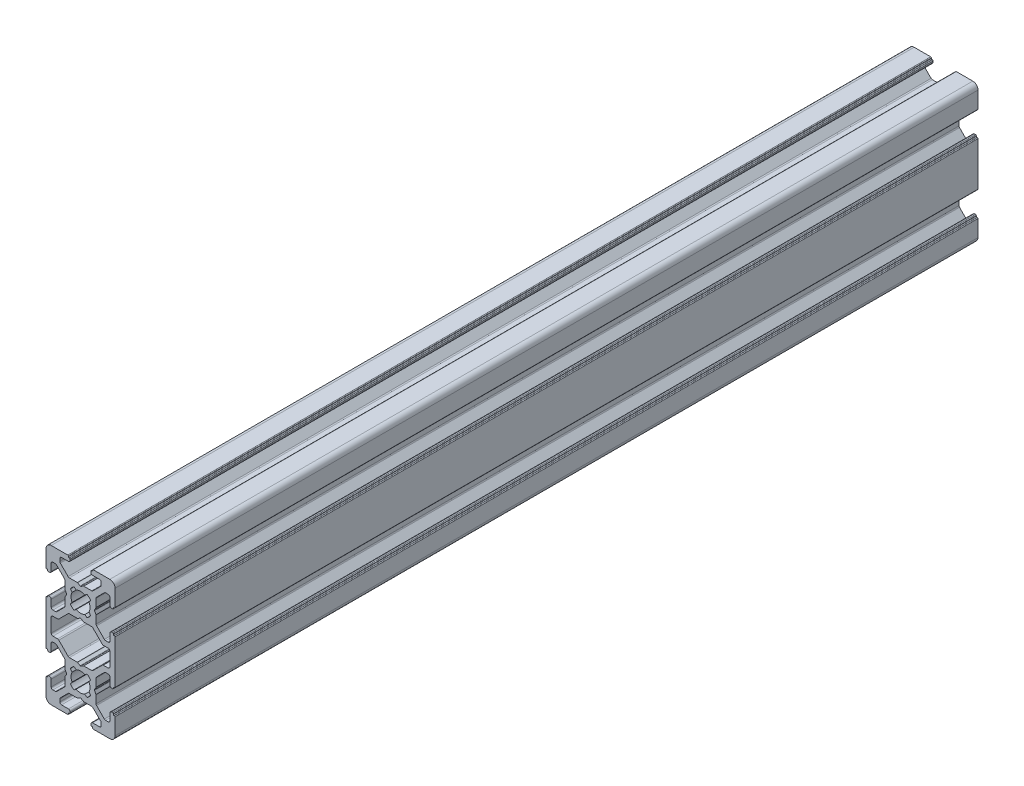
SolidWorks part; units mm, degrees
ref_plane "Front Plane" through (0, 0, 0) normal (0, 0, 1) x (1, 0, 0)
ref_plane "Top Plane" through (0, 0, 0) normal (0, 1, 0) x (1, 0, 0)
ref_plane "Right Plane" through (0, 0, 0) normal (1, 0, 0) x (0, 0, -1)
sketch "Sketch1" plane through (0, 0, 0) normal (0, 0, 1) x (1, 0, 0)
  line L0 (10, -3.75) -> (10, -8.5)
  line L1 (8.5, -3.55) -> (8.5, -5.5)
  line L2 (9.5, -3.25) -> (9.5, -3.35)
  line L3 (9.7, -3.55) -> (9.8, -3.55)
  line L4 (9, -3.05) -> (9.3, -3.05)
  line L5 (9.7, 3.45) -> (9.8, 3.45)
  line L6 (9.5, 3.15) -> (9.5, 3.25)
  line L7 (9, 2.95) -> (9.3, 2.95)
  line L8 (8.5, 3.45) -> (8.5, 5.5)
  line L9 (10, 3.65) -> (10, 10)
  line L10 (-9.7, 3.45) -> (-9.8, 3.45)
  line L11 (-9.5, 3.15) -> (-9.5, 3.25)
  line L12 (-9, 2.95) -> (-9.3, 2.95)
  line L13 (-8.5, 3.45) -> (-8.5, 5.5)
  line L14 (-10, 3.65) -> (-10, 10)
  line L15 (-9.7, -3.55) -> (-9.8, -3.55)
  line L16 (-9.5, -3.25) -> (-9.5, -3.35)
  line L17 (-9, -3.05) -> (-9.3, -3.05)
  line L18 (-8.5, -3.55) -> (-8.5, -5.5)
  line L19 (-10, -3.75) -> (-10, -8.5)
  line L20 (-3.7, -10) -> (-8.5, -10)
  line L21 (-3.5, -8.5) -> (-5.5, -8.5)
  line L22 (-3.2, -9.5) -> (-3.3, -9.5)
  line L23 (-3.5, -9.7) -> (-3.5, -9.8)
  line L24 (-3, -9) -> (-3, -9.3)
  line L25 (3.7, -10) -> (8.5, -10)
  line L26 (3.5, -9.7) -> (3.5, -9.8)
  line L27 (3.2, -9.5) -> (3.3, -9.5)
  line L28 (3, -9) -> (3, -9.3)
  line L29 (3.5, -8.5) -> (5.5, -8.5)
  line L30 (-9.7, 23.5) -> (-9.8, 23.5)
  line L31 (-9.5, 23.2) -> (-9.5, 23.3)
  line L32 (-9, 23) -> (-9.3, 23)
  line L33 (-8.5, 23.5) -> (-8.5, 25.55)
  line L34 (-10, 23.7) -> (-10, 28.5)
  line L35 (-9.7, 16.5) -> (-9.8, 16.5)
  line L36 (-9.5, 16.8) -> (-9.5, 16.7)
  line L37 (-9, 17) -> (-9.3, 17)
  line L38 (-8.5, 16.5) -> (-8.5, 14.55)
  line L39 (-10, 16.3) -> (-10, 10)
  line L40 (10, 16.3) -> (10, 10)
  line L41 (8.5, 16.5) -> (8.5, 14.5)
  line L42 (9.5, 16.8) -> (9.5, 16.7)
  line L43 (9.7, 16.5) -> (9.8, 16.5)
  line L44 (9, 17) -> (9.3, 17)
  line L45 (9.7, 23.5) -> (9.8, 23.5)
  line L46 (9.5, 23.2) -> (9.5, 23.3)
  line L47 (9, 23) -> (9.3, 23)
  line L48 (8.5, 23.5) -> (8.5, 25.5)
  line L49 (10, 23.7) -> (10, 28.5)
  line L50 (-3.7, 30) -> (-8.5, 30)
  line L51 (-3.5, 28.5) -> (-5.5, 28.5)
  line L52 (-3, 29) -> (-3, 29.3)
  line L53 (-3.2, 29.5) -> (-3.3, 29.5)
  line L54 (-3.5, 29.7) -> (-3.5, 29.8)
  line L55 (3.7, 30) -> (8.5, 30)
  line L56 (3.5, 28.5) -> (5.5, 28.5)
  line L57 (3.2, 29.5) -> (3.3, 29.5)
  line L58 (3.5, 29.7) -> (3.5, 29.8)
  line L59 (3, 29) -> (3, 29.3)
  line L60 (2.4453, 18.7418) -> (2.9477, 18.1129)
  line L61 (1.2582, 17.5547) -> (1.8871, 17.0523)
  line L62 (-1.2582, 17.5547) -> (-1.8871, 17.0523)
  line L63 (-2.4453, 18.7418) -> (-2.9477, 18.1129)
  line L64 (-2.4453, 21.2582) -> (-2.9477, 21.8871)
  line L65 (-1.2582, 22.4453) -> (-1.8871, 22.9477)
  line L66 (3.5859, 24.6465) -> (5.8536, 26.9142)
  line L67 (4.6464, 23.5858) -> (6.9142, 25.8536)
  line L68 (4.5, 23.2322) -> (4.5, 20.9536)
  line L69 (4.4732, 20.8536) -> (4.0381, 20.1)
  line L70 (4.4732, 19.1464) -> (4.0381, 19.9)
  line L71 (4.5, 16.7678) -> (4.5, 19.0464)
  line L72 (7.2678, 26) -> (8, 26)
  line L73 (7.2678, 14) -> (8, 14)
  line L74 (2.4453, 21.2582) -> (2.9477, 21.8871)
  line L75 (4.6464, 16.4142) -> (6.9142, 14.1464)
  line L76 (3.2322, 15.5) -> (0.9536, 15.5)
  line L77 (0.8536, 15.5268) -> (0.1, 15.9619)
  line L78 (-0.8536, 15.5268) -> (-0.1, 15.9619)
  line L79 (-3.2322, 15.5) -> (-0.9536, 15.5)
  line L80 (3.5858, 15.3535) -> (6.2929, 12.6464)
  line L81 (-3.5858, 15.3535) -> (-6.2929, 12.6464)
  line L82 (-4.5, 16.7678) -> (-4.5, 19.0464)
  line L83 (-4.4732, 19.1464) -> (-4.0381, 19.9)
  line L84 (-4.4732, 20.8536) -> (-4.0381, 20.1)
  line L85 (-4.5, 23.2322) -> (-4.5, 20.9536)
  line L86 (-7.2178, 14.05) -> (-8, 14.05)
  line L87 (-7.3178, 26.05) -> (-8, 26.05)
  line L88 (-4.6464, 16.4142) -> (-6.8642, 14.1964)
  line L89 (-4.6464, 23.5858) -> (-6.9642, 25.9036)
  line L90 (1.2582, 22.4453) -> (1.8871, 22.9477)
  line L91 (-3.5859, 24.6465) -> (-5.8536, 26.9142)
  line L92 (6, 27.2678) -> (6, 28)
  line L93 (-6, 27.2678) -> (-6, 28)
  line L94 (3.2323, 24.5) -> (0.9537, 24.5)
  line L95 (0.8537, 24.4733) -> (0.1, 24.0381)
  line L96 (-0.8537, 24.4733) -> (-0.1, 24.0381)
  line L97 (-3.2323, 24.5) -> (-0.9537, 24.5)
  line L98 (-3.2322, -4.5) -> (-0.9536, -4.5)
  line L99 (-0.8536, -4.4732) -> (-0.1, -4.0381)
  line L100 (0.8536, -4.4732) -> (0.1, -4.0381)
  line L101 (3.2322, -4.5) -> (0.9536, -4.5)
  line L102 (-6, -7.2678) -> (-6, -8)
  line L103 (6, -7.2678) -> (6, -8)
  line L104 (-3.5858, -4.6464) -> (-5.8536, -6.9142)
  line L105 (1.2582, -2.4453) -> (1.8871, -2.9477)
  line L106 (-4.6464, -3.5858) -> (-6.9142, -5.8536)
  line L107 (-4.6464, 3.5858) -> (-6.9142, 5.8536)
  line L108 (-7.2678, -6) -> (-8, -6)
  line L109 (-7.2678, 6) -> (-8, 6)
  line L110 (-4.5, -3.2322) -> (-4.5, -0.9536)
  line L111 (-4.4732, -0.8536) -> (-4.0381, -0.1)
  line L112 (-4.4732, 0.8536) -> (-4.0381, 0.1)
  line L113 (-4.5, 3.2322) -> (-4.5, 0.9536)
  line L114 (-3.586, 4.6466) -> (-6.2929, 7.3535)
  line L115 (3.586, 4.6466) -> (6.2929, 7.3535)
  line L116 (-3.2324, 4.5001) -> (-0.9538, 4.5001)
  line L117 (-0.8538, 4.4733) -> (-0.1, 4.0381)
  line L118 (0.8538, 4.4733) -> (0.1, 4.0381)
  line L119 (3.2324, 4.5001) -> (0.9538, 4.5001)
  line L120 (4.6464, 3.5858) -> (6.9142, 5.8536)
  line L121 (2.4453, -1.2582) -> (2.9477, -1.8871)
  line L122 (7.2678, 6) -> (8, 6)
  line L123 (7.2678, -6) -> (8, -6)
  line L124 (4.5, 3.2322) -> (4.5, 0.9536)
  line L125 (4.4732, 0.8536) -> (4.0381, 0.1)
  line L126 (4.4732, -0.8536) -> (4.0381, -0.1)
  line L127 (4.5, -3.2322) -> (4.5, -0.9536)
  line L128 (4.6464, -3.5858) -> (6.9142, -5.8536)
  line L129 (3.5858, -4.6464) -> (5.8536, -6.9142)
  line L130 (-1.2582, -2.4453) -> (-1.8871, -2.9477)
  line L131 (-2.4453, -1.2582) -> (-2.9477, -1.8871)
  line L132 (-2.4453, 1.2582) -> (-2.9477, 1.8871)
  line L133 (-1.2582, 2.4453) -> (-1.8871, 2.9477)
  line L134 (1.2582, 2.4453) -> (1.8871, 2.9477)
  line L135 (2.4453, 1.2582) -> (2.9477, 1.8871)
  line L136 (6.6464, 12.5) -> (8, 12.5)
  line L137 (8.5, 8) -> (8.5, 12)
  line L138 (6.6464, 7.5) -> (8, 7.5)
  line L139 (-6.6464, 7.5) -> (-8, 7.5)
  line L140 (-8.5, 8) -> (-8.5, 12)
  line L141 (-6.6464, 12.5) -> (-8, 12.5)
  line L142 (0, 33.3296) -> (0, -13.4112) construction
  line L143 (-17.1897, 10) -> (16.9575, 10) construction
  line L144 (-17.1897, 0) -> (16.9575, 0) construction
  line L145 (-17.1897, 20) -> (16.9575, 20) construction
  arc A0 (9.5, -3.25) -> (9.3, -3.05) centre (9.3, -3.25) ccw
  arc A1 (10, -3.75) -> (9.8, -3.55) centre (9.8, -3.75) ccw
  arc A2 (9.5, -3.35) -> (9.7, -3.55) centre (9.7, -3.35) ccw
  arc A3 (9, -3.05) -> (8.5, -3.55) centre (9, -3.55) ccw
  arc A4 (9.7, 3.45) -> (9.5, 3.25) centre (9.7, 3.25) ccw
  arc A5 (9.8, 3.45) -> (10, 3.65) centre (9.8, 3.65) ccw
  arc A6 (9.3, 2.95) -> (9.5, 3.15) centre (9.3, 3.15) ccw
  arc A7 (8.5, 3.45) -> (9, 2.95) centre (9, 3.45) ccw
  arc A8 (-9.5, 3.25) -> (-9.7, 3.45) centre (-9.7, 3.25) ccw
  arc A9 (-10, 3.65) -> (-9.8, 3.45) centre (-9.8, 3.65) ccw
  arc A10 (-9.5, 3.15) -> (-9.3, 2.95) centre (-9.3, 3.15) ccw
  arc A11 (-9, 2.95) -> (-8.5, 3.45) centre (-9, 3.45) ccw
  arc A12 (-9.7, -3.55) -> (-9.5, -3.35) centre (-9.7, -3.35) ccw
  arc A13 (-9.8, -3.55) -> (-10, -3.75) centre (-9.8, -3.75) ccw
  arc A14 (-9.3, -3.05) -> (-9.5, -3.25) centre (-9.3, -3.25) ccw
  arc A15 (-8.5, -3.55) -> (-9, -3.05) centre (-9, -3.55) ccw
  arc A16 (-3.2, -9.5) -> (-3, -9.3) centre (-3.2, -9.3) ccw
  arc A17 (-3.7, -10) -> (-3.5, -9.8) centre (-3.7, -9.8) ccw
  arc A18 (-3.3, -9.5) -> (-3.5, -9.7) centre (-3.3, -9.7) ccw
  arc A19 (-3, -9) -> (-3.5, -8.5) centre (-3.5, -9) ccw
  arc A20 (3.5, -9.7) -> (3.3, -9.5) centre (3.3, -9.7) ccw
  arc A21 (3.5, -9.8) -> (3.7, -10) centre (3.7, -9.8) ccw
  arc A22 (3, -9.3) -> (3.2, -9.5) centre (3.2, -9.3) ccw
  arc A23 (3.5, -8.5) -> (3, -9) centre (3.5, -9) ccw
  arc A24 (-9.5, 23.3) -> (-9.7, 23.5) centre (-9.7, 23.3) ccw
  arc A25 (-10, 23.7) -> (-9.8, 23.5) centre (-9.8, 23.7) ccw
  arc A26 (-9.5, 23.2) -> (-9.3, 23) centre (-9.3, 23.2) ccw
  arc A27 (-9, 23) -> (-8.5, 23.5) centre (-9, 23.5) ccw
  arc A28 (-9.7, 16.5) -> (-9.5, 16.7) centre (-9.7, 16.7) ccw
  arc A29 (-9.8, 16.5) -> (-10, 16.3) centre (-9.8, 16.3) ccw
  arc A30 (-9.3, 17) -> (-9.5, 16.8) centre (-9.3, 16.8) ccw
  arc A31 (-8.5, 16.5) -> (-9, 17) centre (-9, 16.5) ccw
  arc A32 (9.5, 16.8) -> (9.3, 17) centre (9.3, 16.8) ccw
  arc A33 (10, 16.3) -> (9.8, 16.5) centre (9.8, 16.3) ccw
  arc A34 (9.5, 16.7) -> (9.7, 16.5) centre (9.7, 16.7) ccw
  arc A35 (9, 17) -> (8.5, 16.5) centre (9, 16.5) ccw
  arc A36 (9.7, 23.5) -> (9.5, 23.3) centre (9.7, 23.3) ccw
  arc A37 (9.8, 23.5) -> (10, 23.7) centre (9.8, 23.7) ccw
  arc A38 (9.3, 23) -> (9.5, 23.2) centre (9.3, 23.2) ccw
  arc A39 (8.5, 23.5) -> (9, 23) centre (9, 23.5) ccw
  arc A40 (-3, 29.3) -> (-3.2, 29.5) centre (-3.2, 29.3) ccw
  arc A41 (-3.5, 29.8) -> (-3.7, 30) centre (-3.7, 29.8) ccw
  arc A42 (-3.5, 29.7) -> (-3.3, 29.5) centre (-3.3, 29.7) ccw
  arc A43 (-3.5, 28.5) -> (-3, 29) centre (-3.5, 29) ccw
  arc A44 (3.2, 29.5) -> (3, 29.3) centre (3.2, 29.3) ccw
  arc A45 (3.7, 30) -> (3.5, 29.8) centre (3.7, 29.8) ccw
  arc A46 (3.3, 29.5) -> (3.5, 29.7) centre (3.3, 29.7) ccw
  arc A47 (3, 29) -> (3.5, 28.5) centre (3.5, 29) ccw
  arc A48 (2.4453, 18.7418) -> (2.4453, 21.2582) centre (0, 20) ccw
  arc A49 (-1.2582, 17.5547) -> (1.2582, 17.5547) centre (0, 20) ccw
  arc A50 (-2.4453, 21.2582) -> (-2.4453, 18.7418) centre (0, 20) ccw
  arc A51 (1.8871, 17.0523) -> (2.9477, 18.1129) centre (0, 20) ccw
  arc A52 (-2.9477, 18.1129) -> (-1.8871, 17.0523) centre (0, 20) ccw
  arc A53 (-1.8871, 22.9477) -> (-2.9477, 21.8871) centre (0, 20) ccw
  arc A54 (2.9477, 21.8871) -> (1.8871, 22.9477) centre (0, 20) ccw
  arc A55 (4.0381, 20.1) -> (4.0381, 19.9) centre (4.2113, 20) ccw
  arc A56 (4.5, 19.0464) -> (4.4732, 19.1464) centre (4.3, 19.0464) ccw
  arc A57 (4.4732, 20.8536) -> (4.5, 20.9536) centre (4.3, 20.9536) ccw
  arc A58 (6.9142, 14.1464) -> (7.2678, 14) centre (7.2678, 14.5) ccw
  arc A59 (4.5, 16.7678) -> (4.6464, 16.4142) centre (5, 16.7678) ccw
  arc A60 (4.6464, 23.5858) -> (4.5, 23.2322) centre (5, 23.2322) ccw
  arc A61 (7.2678, 26) -> (6.9142, 25.8536) centre (7.2678, 25.5) ccw
  arc A62 (0.1, 15.9619) -> (-0.1, 15.9619) centre (0, 15.7887) ccw
  arc A63 (-0.9536, 15.5) -> (-0.8536, 15.5268) centre (-0.9536, 15.7) ccw
  arc A64 (0.8536, 15.5268) -> (0.9536, 15.5) centre (0.9536, 15.7) ccw
  arc A65 (-3.2322, 15.5) -> (-3.5858, 15.3535) centre (-3.2322, 15) ccw
  arc A66 (3.5858, 15.3535) -> (3.2322, 15.5) centre (3.2322, 15) ccw
  arc A67 (-4.0381, 19.9) -> (-4.0381, 20.1) centre (-4.2113, 20) ccw
  arc A68 (-4.5, 20.9536) -> (-4.4732, 20.8536) centre (-4.3, 20.9536) ccw
  arc A69 (-4.4732, 19.1464) -> (-4.5, 19.0464) centre (-4.3, 19.0464) ccw
  arc A70 (-6.9642, 25.9036) -> (-7.3178, 26.05) centre (-7.3178, 25.55) ccw
  arc A71 (-4.5, 23.2322) -> (-4.6464, 23.5858) centre (-5, 23.2322) ccw
  arc A72 (-4.6464, 16.4142) -> (-4.5, 16.7678) centre (-5, 16.7678) ccw
  arc A73 (-7.2178, 14.05) -> (-6.8642, 14.1964) centre (-7.2178, 14.55) ccw
  arc A74 (-6, 27.2678) -> (-5.8536, 26.9142) centre (-5.5, 27.2678) ccw
  arc A75 (-3.5859, 24.6465) -> (-3.2323, 24.5) centre (-3.2323, 25) ccw
  arc A76 (3.2323, 24.5) -> (3.5859, 24.6465) centre (3.2323, 25) ccw
  arc A77 (5.8536, 26.9142) -> (6, 27.2678) centre (5.5, 27.2678) ccw
  arc A78 (8.5, 25.5) -> (8, 26) centre (8, 25.5) ccw
  arc A79 (10, 28.5) -> (8.5, 30) centre (8.5, 28.5) ccw
  arc A80 (8, 14) -> (8.5, 14.5) centre (8, 14.5) ccw
  arc A81 (-8.5, 14.55) -> (-8, 14.05) centre (-8, 14.55) ccw
  arc A82 (-8, 26.05) -> (-8.5, 25.55) centre (-8, 25.55) ccw
  arc A83 (6, 28) -> (5.5, 28.5) centre (5.5, 28) ccw
  arc A84 (-8.5, 30) -> (-10, 28.5) centre (-8.5, 28.5) ccw
  arc A85 (-5.5, 28.5) -> (-6, 28) centre (-5.5, 28) ccw
  arc A86 (-0.8537, 24.4733) -> (-0.9537, 24.5) centre (-0.9537, 24.3) ccw
  arc A87 (0.9537, 24.5) -> (0.8537, 24.4733) centre (0.9537, 24.3) ccw
  arc A88 (-0.1, 24.0381) -> (0.1, 24.0381) centre (0, 24.2113) ccw
  arc A89 (1.2582, 22.4453) -> (-1.2582, 22.4453) centre (0, 20) ccw
  arc A90 (-1.2582, -2.4453) -> (1.2582, -2.4453) centre (0, 0) ccw
  arc A91 (0.1, -4.0381) -> (-0.1, -4.0381) centre (0, -4.2113) ccw
  arc A92 (0.8536, -4.4732) -> (0.9536, -4.5) centre (0.9536, -4.3) ccw
  arc A93 (-0.9536, -4.5) -> (-0.8536, -4.4732) centre (-0.9536, -4.3) ccw
  arc A94 (-6, -8) -> (-5.5, -8.5) centre (-5.5, -8) ccw
  arc A95 (-10, -8.5) -> (-8.5, -10) centre (-8.5, -8.5) ccw
  arc A96 (5.5, -8.5) -> (6, -8) centre (5.5, -8) ccw
  arc A97 (-8.5, -5.5) -> (-8, -6) centre (-8, -5.5) ccw
  arc A98 (-8, 6) -> (-8.5, 5.5) centre (-8, 5.5) ccw
  arc A99 (8.5, 5.5) -> (8, 6) centre (8, 5.5) ccw
  arc A100 (8.5, -10) -> (10, -8.5) centre (8.5, -8.5) ccw
  arc A101 (8, -6) -> (8.5, -5.5) centre (8, -5.5) ccw
  arc A102 (6, -7.2678) -> (5.8536, -6.9142) centre (5.5, -7.2678) ccw
  arc A103 (3.5858, -4.6464) -> (3.2322, -4.5) centre (3.2322, -5) ccw
  arc A104 (-3.2322, -4.5) -> (-3.5858, -4.6464) centre (-3.2322, -5) ccw
  arc A105 (-5.8536, -6.9142) -> (-6, -7.2678) centre (-5.5, -7.2678) ccw
  arc A106 (-6.9142, 5.8536) -> (-7.2678, 6) centre (-7.2678, 5.5) ccw
  arc A107 (-4.5, 3.2322) -> (-4.6464, 3.5858) centre (-5, 3.2322) ccw
  arc A108 (-4.6464, -3.5858) -> (-4.5, -3.2322) centre (-5, -3.2322) ccw
  arc A109 (-7.2678, -6) -> (-6.9142, -5.8536) centre (-7.2678, -5.5) ccw
  arc A110 (-4.5, 0.9536) -> (-4.4732, 0.8536) centre (-4.3, 0.9536) ccw
  arc A111 (-4.4732, -0.8536) -> (-4.5, -0.9536) centre (-4.3, -0.9536) ccw
  arc A112 (-4.0381, -0.1) -> (-4.0381, 0.1) centre (-4.2113, 0) ccw
  arc A113 (3.2324, 4.5001) -> (3.586, 4.6466) centre (3.2324, 5.0001) ccw
  arc A114 (-3.586, 4.6466) -> (-3.2324, 4.5001) centre (-3.2324, 5.0001) ccw
  arc A115 (0.9538, 4.5001) -> (0.8538, 4.4733) centre (0.9538, 4.3001) ccw
  arc A116 (-0.8538, 4.4733) -> (-0.9538, 4.5001) centre (-0.9538, 4.3001) ccw
  arc A117 (-0.1, 4.0381) -> (0.1, 4.0381) centre (0, 4.2113) ccw
  arc A118 (6.9142, -5.8536) -> (7.2678, -6) centre (7.2678, -5.5) ccw
  arc A119 (4.5, -3.2322) -> (4.6464, -3.5858) centre (5, -3.2322) ccw
  arc A120 (4.6464, 3.5858) -> (4.5, 3.2322) centre (5, 3.2322) ccw
  arc A121 (7.2678, 6) -> (6.9142, 5.8536) centre (7.2678, 5.5) ccw
  arc A122 (4.5, -0.9536) -> (4.4732, -0.8536) centre (4.3, -0.9536) ccw
  arc A123 (4.4732, 0.8536) -> (4.5, 0.9536) centre (4.3, 0.9536) ccw
  arc A124 (4.0381, 0.1) -> (4.0381, -0.1) centre (4.2113, 0) ccw
  arc A125 (1.8871, -2.9477) -> (2.9477, -1.8871) centre (0, 0) ccw
  arc A126 (-2.9477, -1.8871) -> (-1.8871, -2.9477) centre (0, 0) ccw
  arc A127 (-1.8871, 2.9477) -> (-2.9477, 1.8871) centre (0, 0) ccw
  arc A128 (2.9477, 1.8871) -> (1.8871, 2.9477) centre (0, 0) ccw
  arc A129 (-2.4453, 1.2582) -> (-2.4453, -1.2582) centre (0, 0) ccw
  arc A130 (1.2582, 2.4453) -> (-1.2582, 2.4453) centre (0, 0) ccw
  arc A131 (2.4453, -1.2582) -> (2.4453, 1.2582) centre (0, 0) ccw
  arc A132 (-6.6464, 12.5) -> (-6.2929, 12.6464) centre (-6.6464, 13) ccw
  arc A133 (-8, 12.5) -> (-8.5, 12) centre (-8, 12) ccw
  arc A134 (-8.5, 8) -> (-8, 7.5) centre (-8, 8) ccw
  arc A135 (-6.2929, 7.3535) -> (-6.6464, 7.5) centre (-6.6464, 7) ccw
  arc A136 (6.2929, 12.6464) -> (6.6464, 12.5) centre (6.6464, 13) ccw
  arc A137 (8.5, 12) -> (8, 12.5) centre (8, 12) ccw
  arc A138 (8, 7.5) -> (8.5, 8) centre (8, 8) ccw
  arc A139 (6.6464, 7.5) -> (6.2929, 7.3535) centre (6.6464, 7) ccw
  dimension "D3" = 5.5
  dimension "D4" = 40
  dimension "D2" = 20
  dimension "D5" = 10
  dimension "D6" = 20
  dimension "D7" = 6
  dimension "D8" = 6
  dimension "D9" = 6
  dimension "D10" = 10
  dimension "D11" = 12
  dimension "D12" = 12
  dimension "D13" = 12
  dimension "D14" = 12
  dimension "D15" = 12
  dimension "D16" = 12
extrude "Extrude1" add sketch "Sketch1" along normal blind 250
